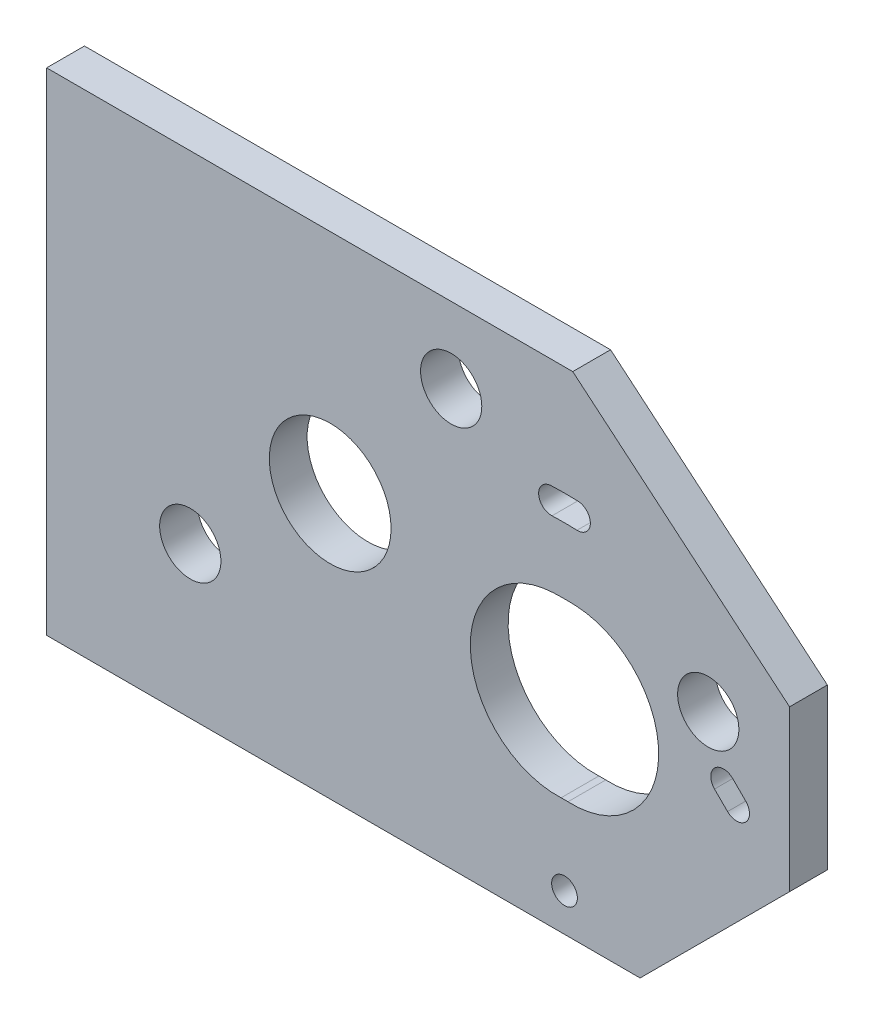
SolidWorks part; units mm, degrees
ref_plane "Front Plane" through (0, 0, 0) normal (0, 0, 1) x (1, 0, 0)
ref_plane "Top Plane" through (0, 0, 0) normal (0, 1, 0) x (1, 0, 0)
ref_plane "Right Plane" through (0, 0, 0) normal (1, 0, 0) x (0, 0, -1)
sketch "Sketch1" plane through (0, 0, 0) normal (0, 0, 1) x (1, 0, 0)
  line L0 (29.2658, 13.8072) -> (30.987, -30) construction
  line L1 (30.987, -30) -> (32.7082, 13.8072) construction
  line L2 (30.987, -30) -> (30.987, 13.841) construction
  line L3 (29.2658, 13.8072) -> (30.987, -30) construction
  line L4 (30.987, -30) -> (32.7082, 13.8072) construction
  line L5 (-37.5, 51.7917) -> (-37.5, -35) construction
  line L6 (-37.5, -35) -> (80.433, -35) construction
  line L7 (30.987, -8.0795) -> (52.0298, -7.2343) construction
  line L8 (30.987, -8.0795) -> (53.7512, -8.954) construction
  line L9 (53.2312, -6.0316) -> (54.9527, -7.7513)
  line L10 (52.5497, -10.1567) -> (50.8283, -8.437)
  line L11 (30.987, -8.0795) -> (50, 0) construction
  line L12 (32.079, 30) -> (-37.5, 30)
  line L13 (-37.5, 30) -> (-37.5, -35)
  line L14 (-37.5, -35) -> (40.987, -35)
  line L15 (40.987, -35) -> (60.7512, -15.2358)
  line L16 (60.7512, -15.2358) -> (60.7512, 5.9412)
  line L17 (60.7512, 5.9412) -> (32.079, 30)
  line L18 (30.0308, -8.1004) -> (30.987, -30) construction
  line L19 (30.987, -30) -> (31.9432, -8.1004) construction
  circle A2 centre (0, 0) radius 10 construction
  circle A3 centre (0, 0) radius 2.5 construction
  circle A4 centre (0, 0) radius 17.8254 construction
  circle A5 centre (16, 20) radius 4.05
  circle A6 centre (50, 0) radius 4.05
  circle A7 centre (-18.5, -15) radius 4.05
  arc A9 (29.2658, 13.8072) -> (32.7082, 13.8072) centre (30.987, -30) cw construction
  arc A10 (29.1991, 15.5059) -> (32.7749, 15.5059) centre (30.987, -30) cw
  arc A11 (29.3326, 12.1085) -> (32.6414, 12.1085) centre (30.987, -30) cw
  arc A12 (29.1991, 15.5059) -> (29.3326, 12.1085) centre (29.2658, 13.8072) ccw
  arc A13 (32.7749, 15.5059) -> (32.6414, 12.1085) centre (32.7082, 13.8072) cw
  circle A14 centre (30.987, -30) radius 1.7
  arc A19 (50.8283, -8.437) -> (53.2312, -6.0316) centre (52.0298, -7.2343) cw
  arc A20 (52.5497, -10.1567) -> (54.9527, -7.7513) centre (53.7512, -8.954) ccw
  circle A21 centre (30.987, -8.0795) radius 4.4563 construction
  circle A23 centre (0, 0) radius 8.05
  arc A25 (29.5292, 3.3887) -> (32.4448, 3.3887) centre (30.987, -30) cw
  arc A26 (30.5325, -19.5894) -> (31.4415, -19.5894) centre (30.987, -30) cw
  arc A27 (29.5292, 3.3887) -> (30.5325, -19.5894) centre (30.0308, -8.1004) ccw
  arc A28 (32.4448, 3.3887) -> (31.4415, -19.5894) centre (31.9432, -8.1004) cw
  arc A29 (30.0308, -8.1004) -> (31.9432, -8.1004) centre (30.987, -30) cw construction
  point P14 (30.987, 13.841)
  point P15 (30.987, -8.0795)
  point P17 (0, 0)
  point P24 (30.987, 12.141)
  point P50 (30.987, -8.0795)
  dimension "D1" = 35.6507
  dimension "D2" = 20
  dimension "D3" = 5
  dimension "D4" = 8.1
  dimension "D12" = 1.7
  dimension "D20" = 8.9127
  dimension "D28" = 16.1
  dimension "D29" = 11.5
  dimension "D5" = 16
  dimension "D6" = 20
  dimension "D7" = 34
  dimension "D8" = 15
  dimension "D9" = 18.5
  dimension "D10" = 4.5
  dimension "D11" = 43.841
  dimension "D13" = 32.023
  dimension "D14" = 19
  dimension "D15" = 20
  dimension "D17" = 92.3
  dimension "D16" = 4.5
  dimension "D18" = 21.0597
  dimension "D19" = 22.781
  dimension "D21" = 5
  dimension "D22" = 140
  dimension "D23" = 135
  dimension "D24" = 10
  dimension "D25" = 7
  dimension "D26" = 12
  dimension "D27" = 10
  dimension "D30" = 5
extrude "Boss-Extrude1" add sketch "Sketch1" along normal blind 5
equation "\"D1@Sketch1\"=(16*3.5*2)/pi"
